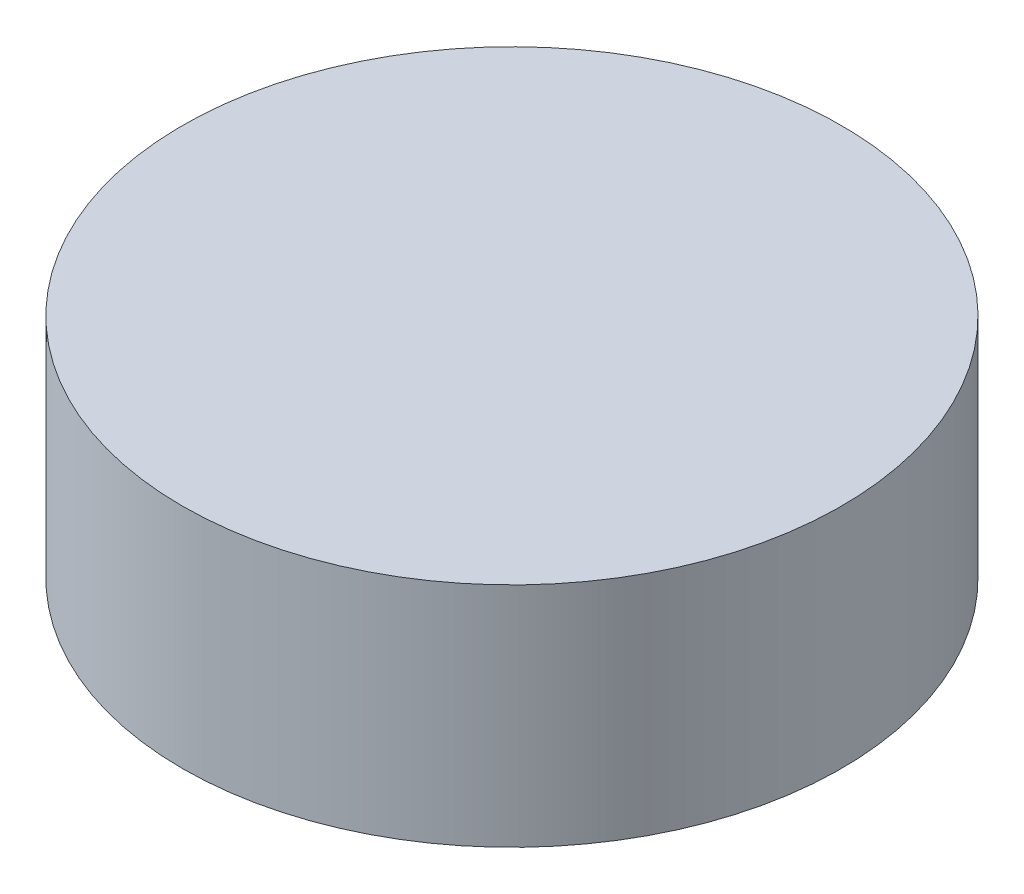
SolidWorks part; units mm, degrees
material "PETG"
ref_plane "Спереди" through (0, 0, 0) normal (0, 0, 1) x (1, 0, 0)
ref_plane "Сверху" through (0, 0, 0) normal (0, 1, 0) x (1, 0, 0)
ref_plane "Справа" through (0, 0, 0) normal (1, 0, 0) x (0, 0, -1)
sketch "Эскиз1" plane through (0, 0, 0) normal (0, 1, 0) x (1, 0, 0)
  circle A0 centre (0, 0) radius 7.25
  dimension "D1" = 14.5
extrude "Бобышка-Вытянуть1" add sketch "Эскиз1" along normal blind 5
